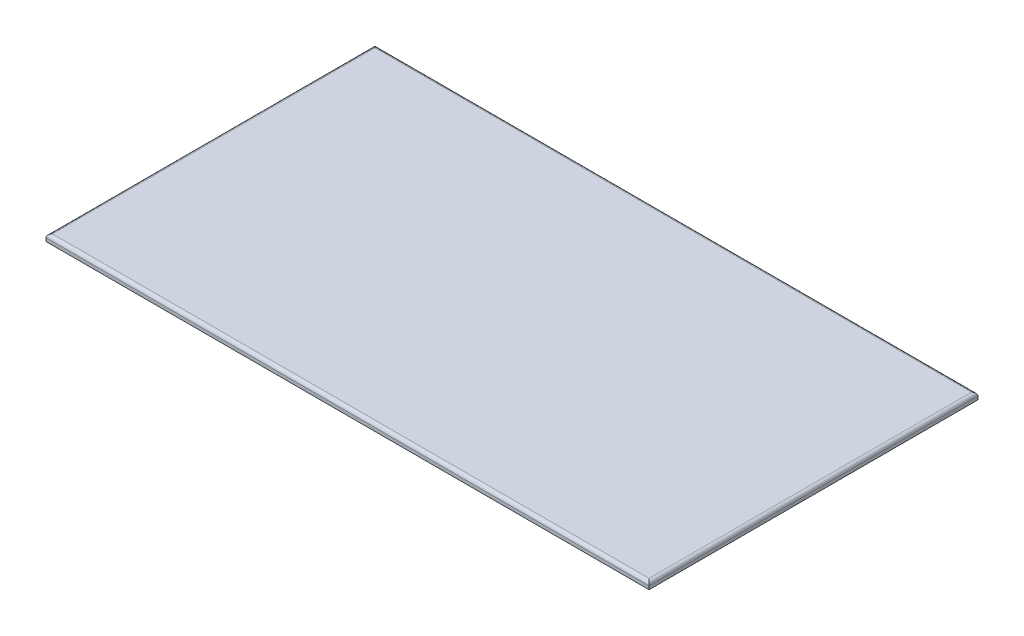
SolidWorks part; units mm, degrees
ref_plane "Front Plane" through (0, 0, 0) normal (0, 0, 1) x (1, 0, 0)
ref_plane "Top Plane" through (0, 0, 0) normal (0, 1, 0) x (1, 0, 0)
ref_plane "Right Plane" through (0, 0, 0) normal (1, 0, 0) x (0, 0, -1)
sketch "Sketch1" plane through (0, 0, 0) normal (0, 1, 0) x (1, 0, 0)
  line L1 (0, 0) -> (550, 0)
  line L2 (0, 0) -> (0, 300)
  line L3 (0, 300) -> (550, 300)
  line L4 (550, 0) -> (550, 300)
  dimension "D1" = 550
  dimension "D2" = 300
extrude "Boss-Extrude1" add sketch "Sketch1" along normal blind 6
fillet "Fillet1" radius 3 4 edges at (275, 6, -300) (550, 6, -150) (275, 6, 0) (0, 6, -150)
sketch "Sketch3" plane through (0, 0, 0) normal (0, -1, 0) x (1, 0, 0)
  line L0 (525, -25) -> (25, -25)
  line L1 (25, -25) -> (25, -275)
  line L2 (25, -275) -> (525, -275)
  line L3 (525, -275) -> (525, -25)
  line L4 (0, 0) -> (0, -300)
  line L5 (0, -300) -> (550, -300)
  line L6 (550, -300) -> (550, 0)
  line L7 (550, 0) -> (0, 0)
  line L8 (0, 0) -> (0, -300)
  line L9 (0, -300) -> (550, -300)
  line L10 (550, -300) -> (550, 0)
  line L11 (550, 0) -> (0, 0)
  dimension "D1" = 0
  dimension "D2" = 25
extrude "Boss-Extrude2" add sketch "Sketch3" along normal blind 26 contours L2 L3 L0 L1
fillet "Fillet2" radius 6 8 edges at (25, -26, -150) (275, -26, -25) (525, -26, -150) (275, -26, -275) (25, -13, -25) (25, -13, -275) (525, -13, -275) (525, -13, -25)
sketch "Sketch4" plane through (0, 6, 0) normal (0, 1, 0) x (1, 0, 0)
  line L0 (222.8792, 64.8207) -> (212.5208, 260.1726) construction
  line L1 (238.7697, 45.67) -> (238.7697, 215.67) construction
